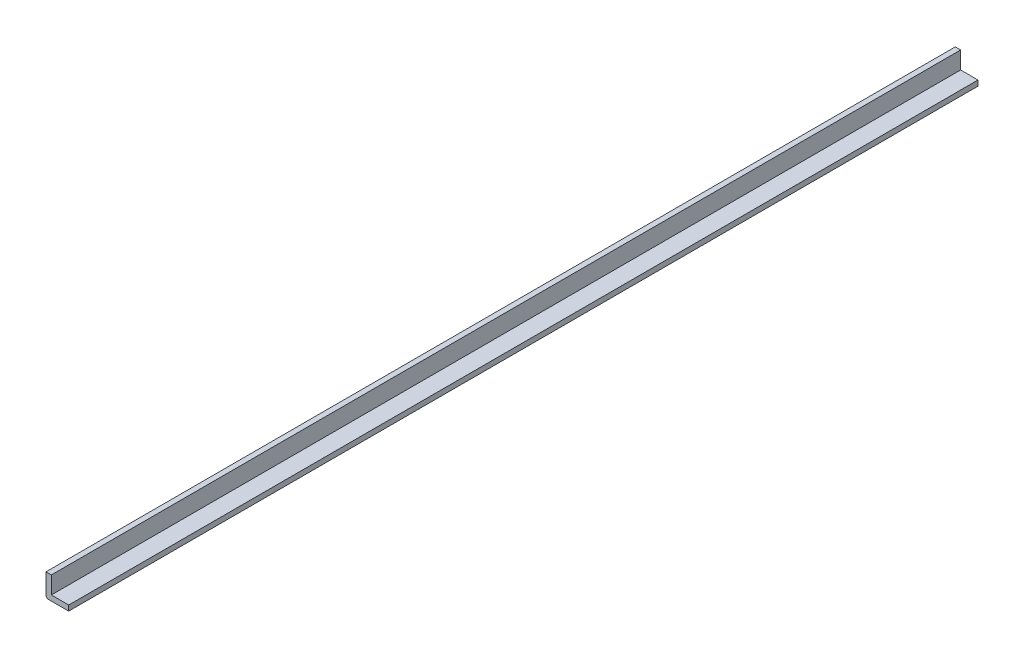
SolidWorks part; units mm, degrees
material "7075-T6 (SN)"
ref_plane "Front Plane" through (0, 0, 0) normal (0, 0, 1) x (1, 0, 0)
ref_plane "Top Plane" through (0, 0, 0) normal (0, 1, 0) x (1, 0, 0)
ref_plane "Right Plane" through (0, 0, 0) normal (1, 0, 0) x (0, 0, -1)
sketch "Sketch1" plane through (0, 0, 0) normal (0, 0, 1) x (1, 0, 0)
  line L0 (0, 0) -> (-8.5, 0)
  line L1 (-8.5, 0) -> (-8.5, 8.5)
  line L2 (-8.5, 8.5) -> (-6.5, 8.5)
  line L3 (-6.5, 8.5) -> (-6.5, 2)
  line L4 (-6.5, 2) -> (0, 2)
  line L5 (0, 2) -> (0, 0)
  dimension "D1" = 2
  dimension "D2" = 2
  dimension "D3" = 8.5
  dimension "D4" = 8.5
extrude "Boss-Extrude1" add sketch "Sketch1" along normal blind 340.5
fillet "Fillet1" radius 1 1 edges at (-8.5, 0, 170.25)
ref_plane "Plane1" through (0, 0, 170.25) normal (0, 0, 1) x (1, 0, 0)
equation "\"thickness\"= 2mm"
equation "\"D1@Sketch1\"=\"thickness\""
equation "\"D2@Sketch1\"=\"D1@Sketch1\""
equation "\"D4@Sketch1\"=\"D3@Sketch1\""
